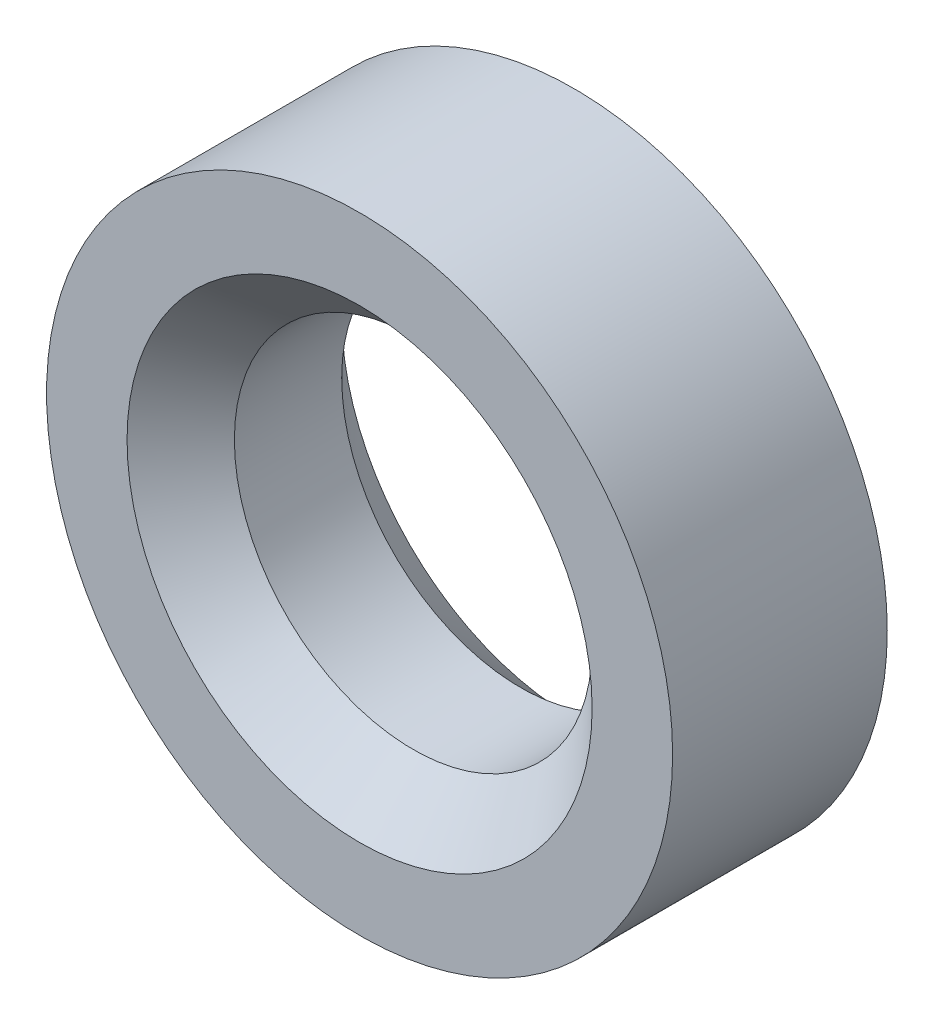
SolidWorks part; units mm, degrees
ref_plane "Front Plane" through (0, 0, 0) normal (0, 0, 1) x (1, 0, 0)
ref_plane "Top Plane" through (0, 0, 0) normal (0, 1, 0) x (1, 0, 0)
ref_plane "Right Plane" through (0, 0, 0) normal (1, 0, 0) x (0, 0, -1)
sketch "Sketch1" plane through (0, 0, 0) normal (0, 0, 1) x (1, 0, 0)
  circle A0 centre (0, 0) radius 2
  circle A1 centre (0, 0) radius 3.5
  dimension "D1" = 4
  dimension "D2" = 7
extrude "Boss-Extrude1" add sketch "Sketch1" along normal mid plane 2.4 contours A1
chamfer "Chamfer1" distance 0.6 angle 45 2 edges at (2, 0, -1.2) (2, 0, 1.2)
